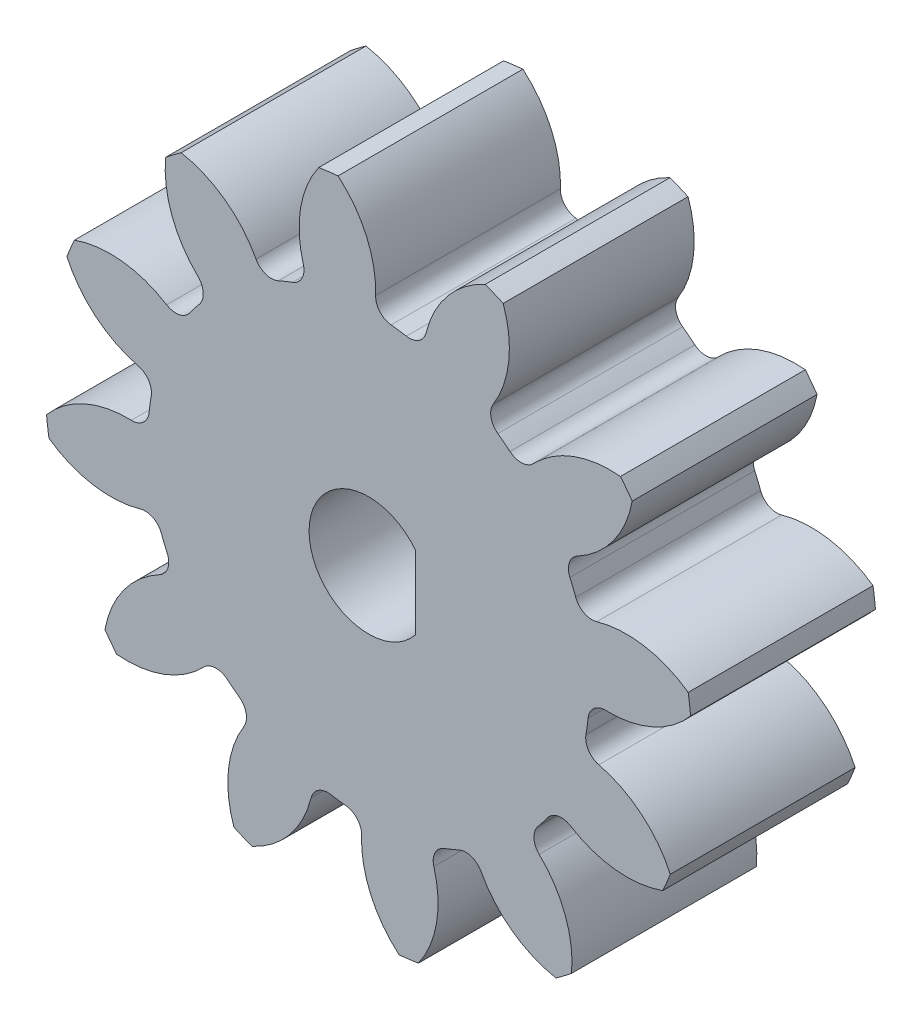
SolidWorks part; units mm, degrees
ref_plane "Front" through (0, 0, 0) normal (0, 0, 1) x (1, 0, 0)
ref_plane "Top" through (0, 0, 0) normal (0, 1, 0) x (1, 0, 0)
ref_plane "Right" through (0, 0, 0) normal (1, 0, 0) x (0, 0, -1)
sketch "Sketch3" plane through (0, 0, 0) normal (0, 0, 1) x (1, 0, 0)
  circle A0 centre (0, 0) radius 14
  dimension "od" = 28
extrude "gearBody" add sketch "Sketch3" along normal blind 8
sketch "Sketch2" plane through (0, 0, 0) normal (0, 0, 1) x (1, 0, 0)
  line L0 (0, 0) -> (10.418, 4.3153) construction
  line L1 (13.239, -5.5064) -> (0, 0) construction
  line L2 (0, 0) -> (36.3143, 0) construction
  line L3 (12, -0.0271) -> (11.5579, -3.2271) construction
  line L5 (11.779, -1.6271) -> (0, 0) construction
  line L7 (0, 0) -> (11.2763, 0) construction
  arc A0 (11.274, -0.2263) -> (10.9132, -2.8385) centre (0, 0) ccw construction
  arc A1 (13.9376, 1.3202) -> (13.0578, -5.0492) centre (0, 0) ccw construction
  arc A2 (12, -0.0271) -> (11.5579, -3.2271) centre (0, 0) ccw construction
  arc A3 (9.4079, -1.6368) -> (9.4993, -0.975) centre (0, 0) ccw
  arc A4 (13.239, -5.5064) -> (9.9655, -2.4911) centre (8.858, -6.9779) ccw
  arc A5 (13.239, -5.5064) -> (14.236, 1.7111) centre (0, 0) ccw
  arc A6 (14.236, 1.7111) -> (10.2676, -0.3038) centre (10.418, 4.3153) cw
  arc A7 (9.4993, -0.975) -> (10.2676, -0.3038) centre (10.2433, -1.0513) cw
  arc A8 (9.9655, -2.4911) -> (9.4079, -1.6368) centre (10.1447, -1.7649) cw
  point P6 (14.236, 1.7111)
  point P22 (13.239, -5.5064)
  dimension "baseDia" = 22.5526
  dimension "od" = 28
  dimension "pd" = 24
  dimension "rd" = 19.0984
  dimension "rFillet" = 0.7479
  dimension "pointX" = 14.236
  dimension "pointY" = 1.7111
  dimension "CTT" = 3.2
  dimension "flankCenterAngle" = 22.5
extrude "toothCut" cut sketch "Sketch2" along normal through all
pattern_circular "CirPattern1" count 12 over 360 about axis through (0, 0, 0) along (0, 0, 1) of "toothCut"
sketch "hub1Dia" plane through (0, 0, 0) normal (0, 0, -1) x (-1, 0, 0)
  line L0 (-2.025, -1.5906) -> (-2.025, 1.5906)
  arc A1 (-2.025, -1.5906) -> (-2.025, 1.5906) centre (0, 0) ccw
  point P8 (2.575, 0)
  dimension "D1" = 5.15
  dimension "D2" = 4.6
sketch "hub2Dia" plane through (0, 0, 8) normal (0, 0, 1) x (1, 0, 0)
  circle A0 centre (0, 0) radius 0.5
  dimension "hub2dia" = 1
sketch "boreDia" plane through (0, 0, 0) normal (0, 0, 1) x (1, 0, 0)
  circle A0 centre (0, 0) radius 6
  dimension "boreDia" = 12
extrude "bore" [suppressed] cut sketch "boreDia" against normal mid plane 25400
extrude "Cut-Extrude1" cut sketch "hub1Dia" against normal up to surface (8 mm away) up to face at (0, 0, 8)
chamfer "Chamfer1" distance 1 angle 45 2 edges at (2.025, 0, 0) (-2.575, 0, 0)
